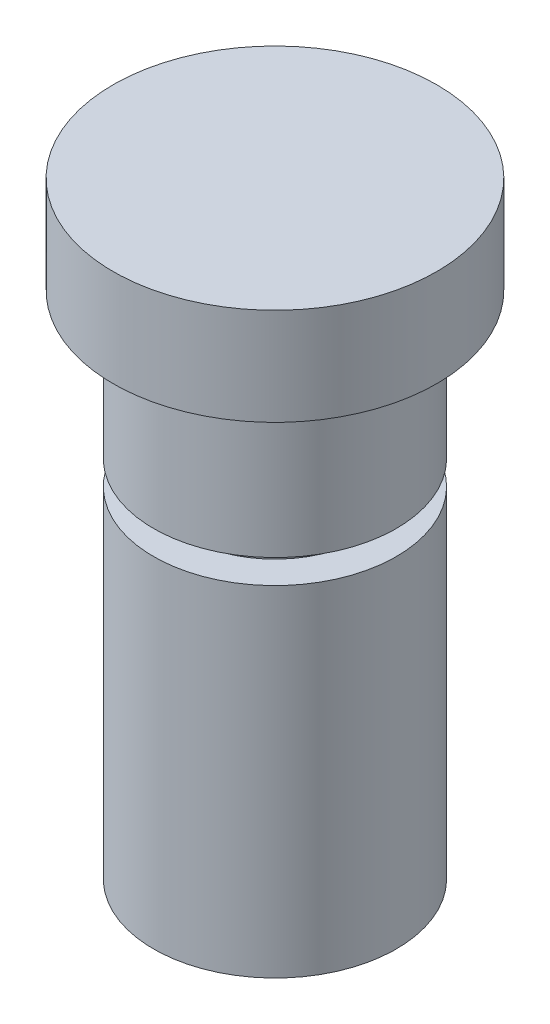
SolidWorks part; units mm, degrees
ref_plane "Front Plane" through (0, 0, 0) normal (0, 0, 1) x (1, 0, 0)
ref_plane "Top Plane" through (0, 0, 0) normal (0, 1, 0) x (1, 0, 0)
ref_plane "Right Plane" through (0, 0, 0) normal (1, 0, 0) x (0, 0, -1)
sketch "SK_EStop" plane through (0, 0, 0) normal (0, 0, 1) x (1, 0, 0)
  line L0 (0, -45) -> (15, -45)
  line L1 (15, -45) -> (15, -3)
  line L2 (15, -3) -> (11, -3)
  line L3 (11, -3) -> (11, 0)
  line L4 (11, 0) -> (15, 0)
  line L5 (15, 0) -> (15, 18)
  line L6 (15, 18) -> (20, 18)
  line L7 (20, 18) -> (20, 30)
  line L8 (20, 30) -> (0, 30)
  line L9 (0, 30) -> (0, -45)
  line L10 (0, -50) -> (0, 35) construction
revolve "EStop" add sketch "SK_EStop" angle 360 about L10
